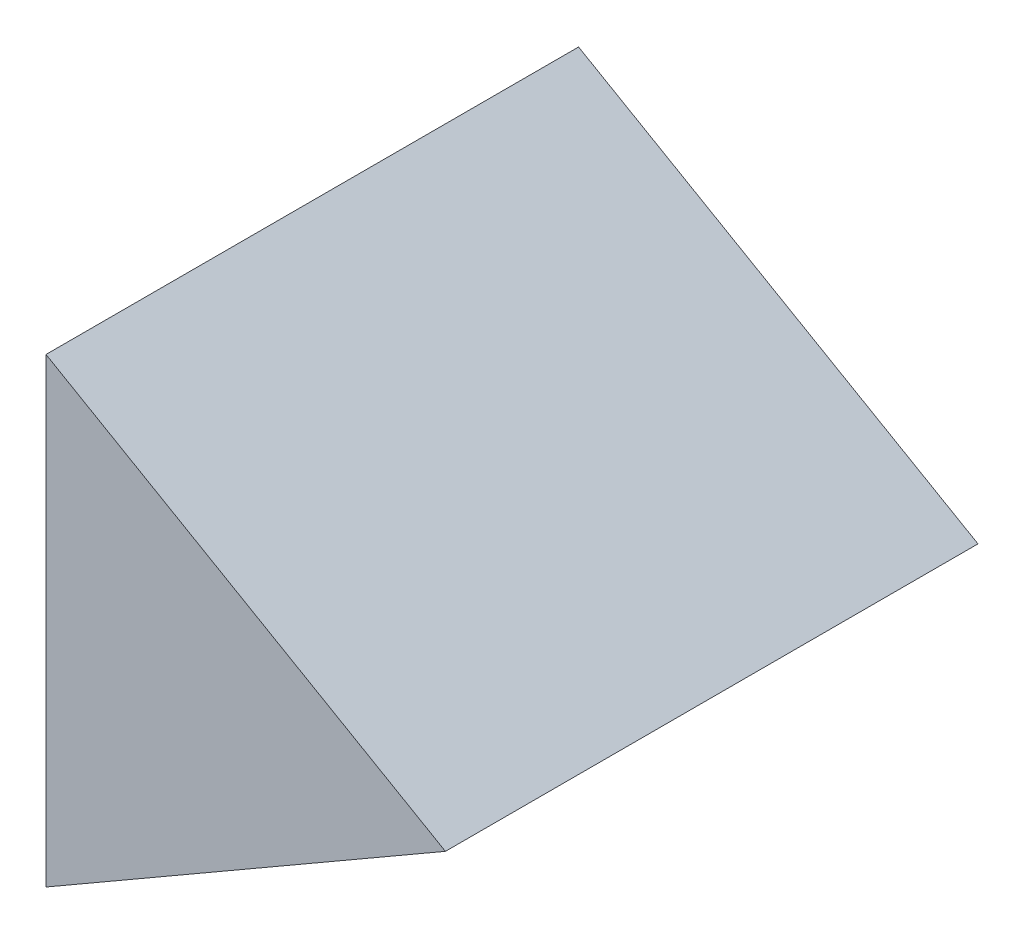
SolidWorks part; units mm, degrees
ref_plane "前视基准面" through (0, 0, 0) normal (0, 0, 1) x (1, 0, 0)
ref_plane "上视基准面" through (0, 0, 0) normal (0, 1, 0) x (1, 0, 0)
ref_plane "右视基准面" through (0, 0, 0) normal (1, 0, 0) x (0, 0, -1)
other "Configuration Table"
sketch "草图1" plane through (0, 0, 0) normal (0, 0, 1) x (1, 0, 0)
  circle A0 centre (0, 0) radius 50
extrude "凸台-拉伸1" add sketch "草图1" along normal blind 300
sketch "草图2" plane through (0, 0, 0) normal (0, 0, 1) x (1, 0, 0)
  line L1 (400, 0) -> (-200, 346.4102)
  line L2 (-200, 346.4102) -> (-200, -346.4102)
  line L3 (-200, -346.4102) -> (400, 0)
  circle A0 centre (0, 0) radius 200 construction
extrude "凸台-拉伸2" add sketch "草图2" along normal blind 800
